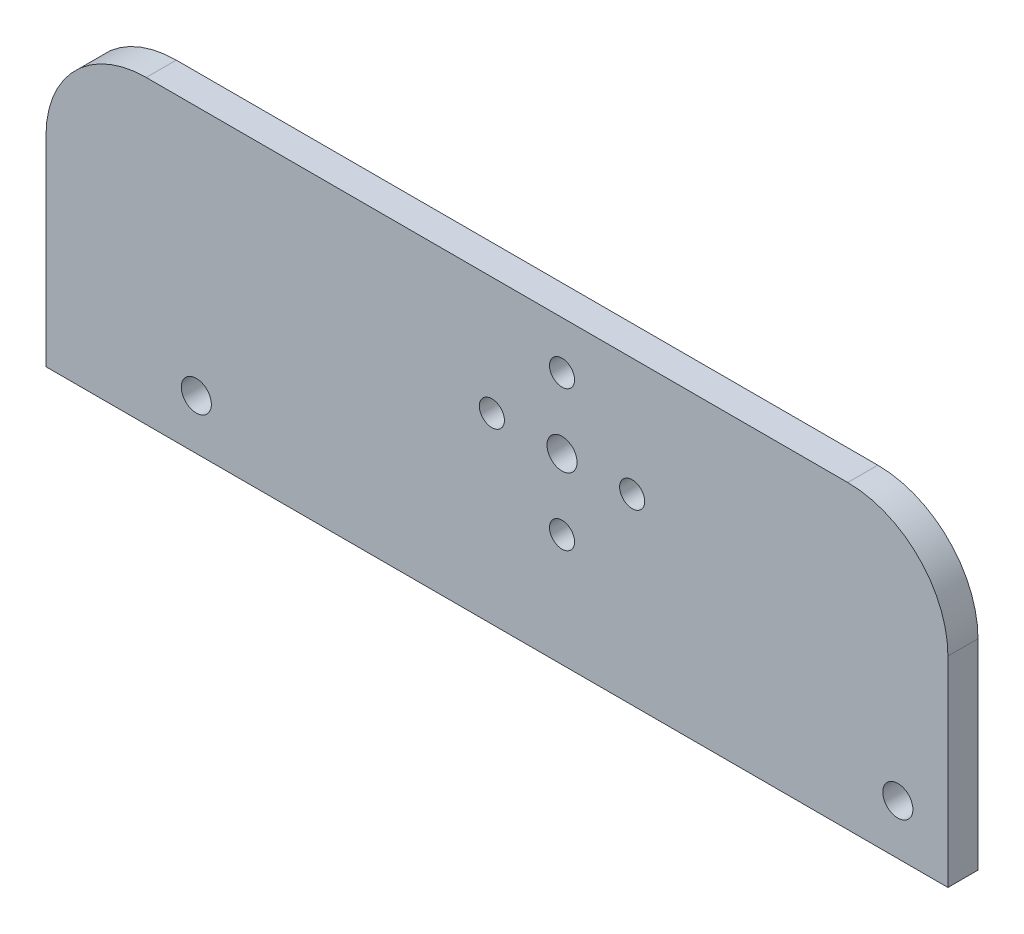
SolidWorks part; units mm, degrees
ref_plane "前视基准面" through (0, 0, 0) normal (0, 0, 1) x (1, 0, 0)
ref_plane "上视基准面" through (0, 0, 0) normal (0, 1, 0) x (1, 0, 0)
ref_plane "右视基准面" through (0, 0, 0) normal (1, 0, 0) x (0, 0, -1)
sketch "草图1" plane through (0, 0, 0) normal (0, 0, 1) x (1, 0, 0)
  line L1 (-45, 15) -> (45, 15)
  line L2 (-45, 15) -> (-45, -15)
  line L3 (-45, -15) -> (45, -15)
  line L4 (45, 15) -> (45, -15)
  line L5 (-45, 15) -> (45, -15) construction
  line L6 (-45, -15) -> (45, 15) construction
  point P0 (0, 0)
  dimension "D1" = 90
  dimension "D2" = 30
extrude "凸台-拉伸1" add sketch "草图1" along normal blind 3
sketch "草图3" plane through (0, 0, 0) normal (0, 0, -1) x (-1, 0, 0)
  circle A0 centre (-6.4923, 3.237) radius 1.5 construction
  circle A1 centre (-13.4923, 3.237) radius 1.25 construction
  circle A2 centre (-6.4923, 10.237) radius 1.25 construction
  circle A3 centre (-6.4923, -3.763) radius 1.25 construction
  circle A4 centre (0.5077, 3.237) radius 1.25 construction
  circle A5 centre (-6.4923, 3.237) radius 1.5
  circle A6 centre (-13.4923, 3.237) radius 1.25
  circle A7 centre (-6.4923, 10.237) radius 1.25
  circle A8 centre (-6.4923, -3.763) radius 1.25
  circle A9 centre (0.5077, 3.237) radius 1.25
extrude "切除-拉伸2" cut sketch "草图3" against normal blind 10
sketch "草图4" plane through (0, 0, 0) normal (0, 0, -1) x (-1, 0, 0)
  circle A2 centre (-40, -10) radius 1.5 construction
  circle A3 centre (30, -10) radius 1.5 construction
  circle A4 centre (-40, -10) radius 1.5
  circle A5 centre (30, -10) radius 1.5
extrude "切除-拉伸3" cut sketch "草图4" against normal blind 10
fillet "圆角1" radius 10 2 edges at (45, 15, 1.5) (-45, 15, 1.5)
